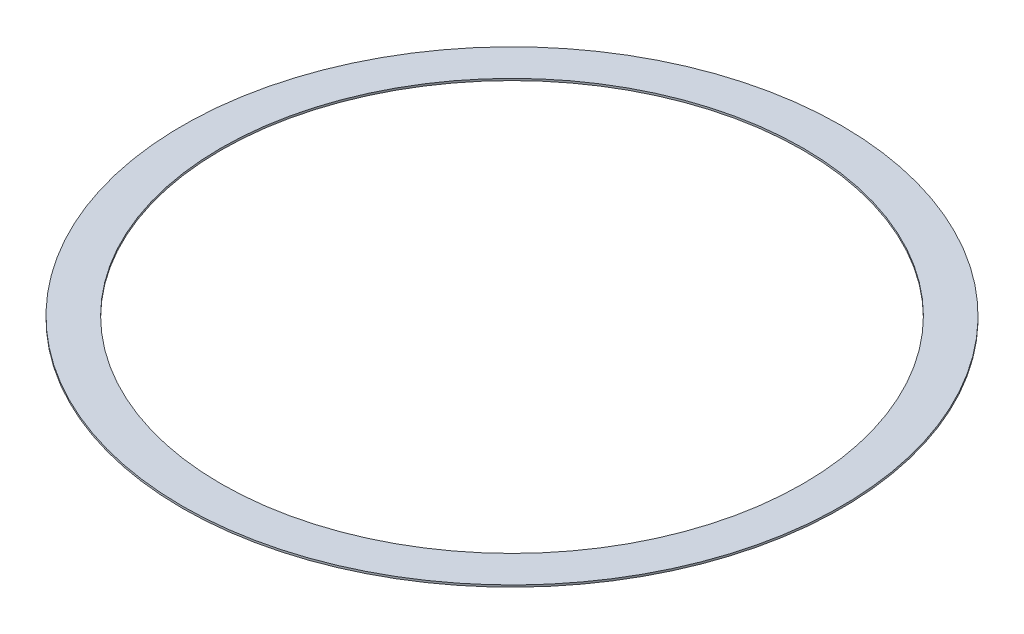
SolidWorks part; units mm, degrees
material "Galvanized Steel"
ref_plane "Front Plane" through (0, 0, 0) normal (0, 0, 1) x (1, 0, 0)
ref_plane "Top Plane" through (0, 0, 0) normal (0, 1, 0) x (1, 0, 0)
ref_plane "Right Plane" through (0, 0, 0) normal (1, 0, 0) x (0, 0, -1)
sketch "Sketch1" plane through (0, 0, 0) normal (0, 1, 0) x (1, 0, 0)
  circle A0 centre (0, 0) radius 426.5
  circle A1 centre (0, 0) radius 376.5
  dimension "D1" = 853
  dimension "D2" = 753
extrude "Boss-Extrude1" add sketch "Sketch1" along normal mid plane 2.5
